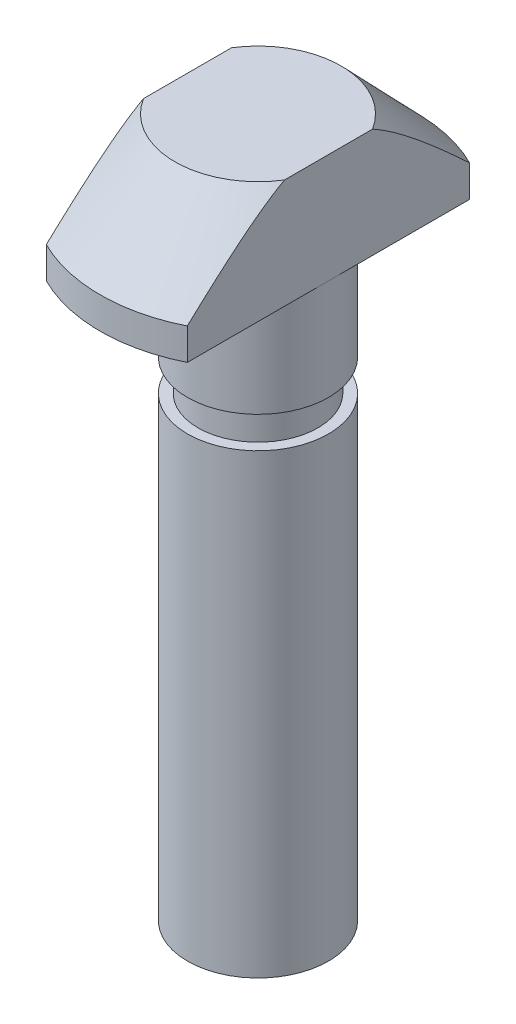
SolidWorks part; units mm, degrees
ref_plane "前视基准面" through (0, 0, 0) normal (0, 0, 1) x (1, 0, 0)
ref_plane "上视基准面" through (0, 0, 0) normal (0, 1, 0) x (1, 0, 0)
ref_plane "右视基准面" through (0, 0, 0) normal (1, 0, 0) x (0, 0, -1)
sketch "草图1" plane through (0, 0, 0) normal (0, 0, 1) x (1, 0, 0)
  line B0 (3.95, 33.2) -> (0, 33.2)
  line B1 (0, 33.2) -> (0, 0)
  line B2 (7.5, 28) -> (3.35, 28)
  line B3 (7.5, 29.5) -> (7.5, 28)
  line B4 (7.5, 29.5) -> (3.95, 33.2)
  line B5 (3.35, 28) -> (3.35, 23.2)
  line B6 (3.35, 21.7) -> (3.35, 0)
  line B7 (0, 0) -> (3.35, 0)
  line B8 (2.85, 23.2) -> (3.35, 23.2)
  line B9 (2.85, 21.7) -> (3.35, 21.7)
  line B10 (2.85, 23.2) -> (2.85, 21.7)
sketch_block_instance "A$C6D1415FF-1"
sketch_block "A$C6D1415FF"
revolve "旋转1" add sketch "草图1" angle 360 about L1
sketch "草图3" plane through (0, 0, 0) normal (0, 0, 1) x (1, 0, 0)
  line L0 (-3.35, 28) -> (-3.35, 23.2) construction
  line L1 (-3.35, 24.821) -> (-10.6953, 24.821)
  line L2 (-3.35, 24.821) -> (-3.35, 33.6407)
  line L3 (-3.35, 33.6407) -> (-10.6953, 33.6407)
  line L4 (-10.6953, 24.821) -> (-10.6953, 33.6407)
  line L5 (3.35, 23.2) -> (3.35, 28) construction
  line L6 (3.35, 24.5417) -> (12.0522, 24.5417)
  line L7 (3.35, 24.5417) -> (3.35, 34.5187)
  line L8 (3.35, 34.5187) -> (12.0522, 34.5187)
  line L9 (12.0522, 24.5417) -> (12.0522, 34.5187)
extrude "切除-拉伸1" cut sketch "草图3" against normal mid plane 100
sketch "草图4" plane through (0, 0, 0) normal (1, 0, 0) x (0, 0, -1)
  line L0 (3.35, 5.4408) -> (1.65, 5.4408)
  line L1 (3.35, 0) -> (3.35, 21.7) construction
  line L3 (1.65, 6.9408) -> (1.65, 5.4408)
  line L6 (1.65, 6.9408) -> (3.35, 8.6408)
  line L7 (3.35, 0) -> (3.35, 21.7) construction
  line L8 (3.35, 8.6408) -> (3.35, 5.4408)
  dimension "D3" = 45
revolve "切除-旋转1" cut sketch "草图4" angle 360 about L0
